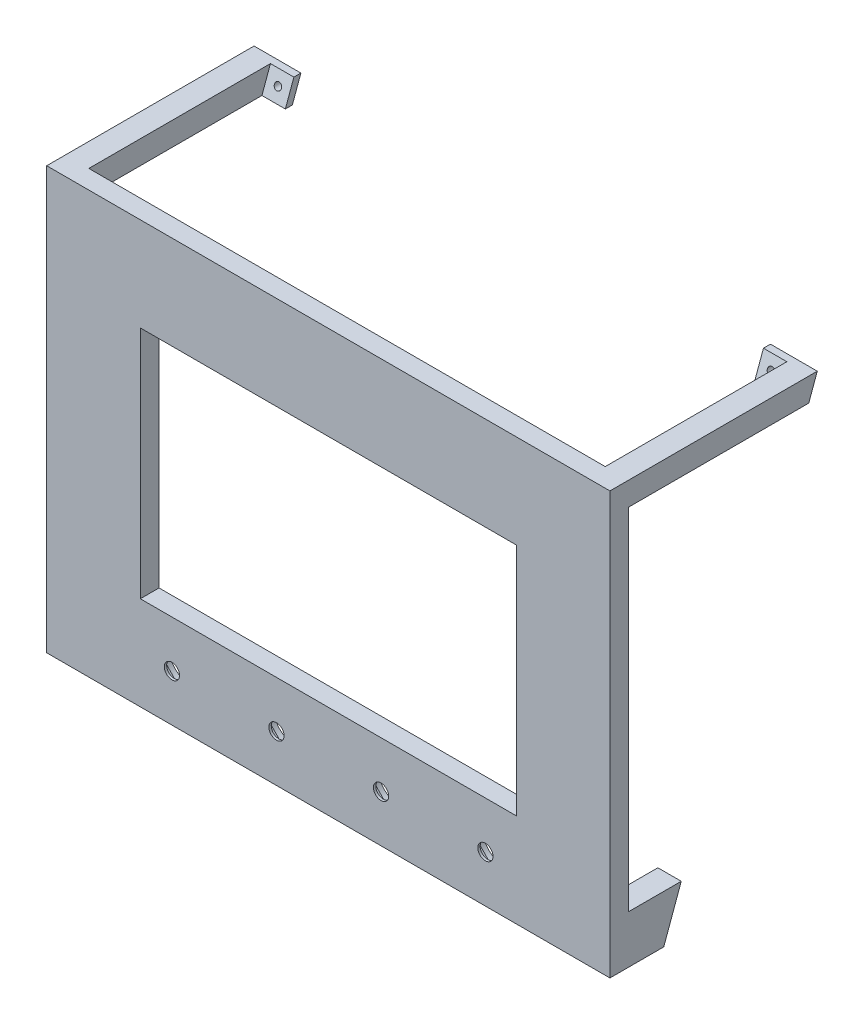
SolidWorks part; units mm, degrees
ref_plane "Front Plane" through (0, 0, 0) normal (0, 0, 1) x (1, 0, 0)
ref_plane "Top Plane" through (0, 0, 0) normal (0, 1, 0) x (1, 0, 0)
ref_plane "Right Plane" through (0, 0, 0) normal (1, 0, 0) x (0, 0, -1)
ref_plane "Plane1" through (0, 0, 0) normal (0, 0, -1) x (-1, 0, 0)
sketch "Sketch1" plane through (0, 0, 0) normal (0, 0, -1) x (-1, 0, 0)
  line L0 (69.5977, -77.75) -> (69.5977, 102.45)
  line L1 (69.5977, 102.45) -> (-171.0023, 102.45)
  line L2 (-171.0023, 102.45) -> (-171.0023, -77.75)
  line L3 (-171.0023, -77.75) -> (69.5977, -77.75)
extrude "Boss-Extrude1" add sketch "Sketch1" against normal blind 8
sketch "Sketch2" plane through (0, 0, 8) normal (0, 0, 1) x (1, 0, 0)
  line L0 (-29.5977, 62.45) -> (-29.5977, -37.75)
  line L1 (-29.5977, -37.75) -> (131.0023, -37.75)
  line L2 (131.0023, -37.75) -> (131.0023, 62.45)
  line L3 (131.0023, 62.45) -> (-29.5977, 62.45)
extrude "Cut-Extrude1" cut sketch "Sketch2" against normal through all
sketch "Sketch3" plane through (0, 0, 0) normal (0, 0, -1) x (-1, 0, 0)
  line L0 (-117.6868, -48.4833) -> (-127.0608, -58.1981)
  line L1 (-127.0608, -58.1981) -> (-117.9217, -67.0167)
  line L2 (-117.9217, -67.0167) -> (-108.5476, -57.3019)
  line L3 (-108.5476, -57.3019) -> (-117.6868, -48.4833)
extrude "Cut-Extrude2" cut sketch "Sketch3" against normal blind 7
sketch "Sketch4" plane through (0, 0, 0) normal (0, 0, -1) x (-1, 0, 0)
  line L0 (6.9392, -58.1981) -> (16.0783, -67.0167)
  line L1 (16.0783, -67.0167) -> (25.4524, -57.3019)
  line L2 (25.4524, -57.3019) -> (16.3132, -48.4833)
  line L3 (16.3132, -48.4833) -> (6.9392, -58.1981)
extrude "Cut-Extrude3" cut sketch "Sketch4" against normal blind 7
sketch "Sketch5" plane through (0, 0, 0) normal (0, 0, -1) x (-1, 0, 0)
  line L0 (-37.7275, -58.1981) -> (-28.5883, -67.0167)
  line L1 (-28.5883, -67.0167) -> (-19.2143, -57.3019)
  line L2 (-19.2143, -57.3019) -> (-28.3534, -48.4833)
  line L3 (-28.3534, -48.4833) -> (-37.7275, -58.1981)
extrude "Cut-Extrude4" cut sketch "Sketch5" against normal blind 7
sketch "Sketch6" plane through (0, 0, 0) normal (0, 0, -1) x (-1, 0, 0)
  line L0 (-82.3941, -58.1981) -> (-73.255, -67.0167)
  line L1 (-73.255, -67.0167) -> (-63.881, -57.3019)
  line L2 (-63.881, -57.3019) -> (-73.0201, -48.4833)
  line L3 (-73.0201, -48.4833) -> (-82.3941, -58.1981)
extrude "Cut-Extrude5" cut sketch "Sketch6" against normal blind 7
hole_wizard "Ø6.5 (6.5) Diameter Hole1" positions "Sketch8" profile "Sketch7" hole size "Ø6.5" standard "ANSI Metric"
sketch "Sketch8" plane through (0, 0, 8) normal (0, 0, 1) x (1, 0, 0)
  point P0 (117.8042, -57.75)
  point P1 (-16.0977, -57.75)
  point P2 (28.569, -57.75)
  point P3 (73.2357, -57.75)
sketch "Sketch7" plane through (117.8042, -57.75, 8) normal (1, 0, 0) x (0, -1, 0)
  line L0 (0, 0) -> (0, 8)
  line L1 (0, 8) -> (3.25, 8)
  line L2 (3.25, 8) -> (3.25, 0)
  line L5 (3.25, 0) -> (0, 0)
  line L11 (0, -6.35) -> (0, 107.95) construction
  dimension "Thru Hole Dia." = 6.5
  dimension "Thru Hole Depth" = 8
sketch "Sketch9" plane through (0, 0, 0) normal (0, 0, -1) x (-1, 0, 0)
  line L0 (-126.9808, -58.2753) -> (-117.9867, -66.9539)
  line L3 (-127.0608, -58.1981) -> (-117.9217, -67.0167) construction
  line L4 (-117.6868, -48.4833) -> (-108.5476, -57.3019)
  line L7 (-108.5476, -57.3019) -> (-117.6868, -48.4833) construction
  line L8 (-117.6868, -48.4833) -> (-127.0608, -58.1981) construction
  line L9 (-117.9217, -67.0167) -> (-108.5476, -57.3019) construction
  circle A0 centre (-117.8042, -57.75) radius 9.2674
  circle A1 centre (-73.2357, -57.75) radius 9.2692
  circle A2 centre (-28.569, -57.75) radius 9.2692
  circle A3 centre (16.0977, -57.75) radius 9.2667
  point P0 (-117.8042, -57.75)
  line M2 (-82.3941, -58.1981) -> (-73.0201, -48.4833)
  line M3 (-73.0201, -48.4833) -> (-63.881, -57.3019)
  line M4 (-63.881, -57.3019) -> (-73.255, -67.0167)
  line M5 (-73.255, -67.0167) -> (-82.3941, -58.1981)
  line M6 (-37.7275, -58.1981) -> (-28.3534, -48.4833)
  line M7 (-28.3534, -48.4833) -> (-19.2143, -57.3019)
  line M8 (-19.2143, -57.3019) -> (-28.5883, -67.0167)
  line M9 (-28.5883, -67.0167) -> (-37.7275, -58.1981)
  line M10 (6.9392, -58.1981) -> (16.3132, -48.4833)
  line M11 (16.3132, -48.4833) -> (25.4524, -57.3019)
  line M12 (25.4524, -57.3019) -> (16.0783, -67.0167)
  line M13 (16.0783, -67.0167) -> (6.9392, -58.1981)
  line M14 (-117.6868, -48.4833) -> (-108.5476, -57.3019)
  line M15 (-108.5476, -57.3019) -> (-117.9217, -67.0167)
  line M16 (-117.9217, -67.0167) -> (-127.0608, -58.1981)
  line M17 (-127.0608, -58.1981) -> (-117.6868, -48.4833)
extrude "Cut-Extrude7" cut sketch "Sketch9" against normal blind 4 contours A0 M14 | A0 M16 | A0 M17 | A0 M15 | A1 M2 M4 M5 | A1 M3 | A2 M6 M8 M9 | A2 M7 | A3 M10 M13 | A3 M12 | A3 M11
sketch "Sketch10" plane through (0, 0, 0) normal (0, 0, -1) x (-1, 0, 0)
  circle A0 centre (-127.0023, 69.25) radius 1.5
  circle A1 centre (29.9977, 69.25) radius 1.5
  circle A2 centre (29.9977, -45.75) radius 1.5
  circle A3 centre (-127.0023, -45.75) radius 1.5
sketch "Sketch12" plane through (171.0023, 0, 0) normal (1, 0, 0) x (0, 0, -1)
  line L0 (0, -77.75) -> (15, -77.75)
  line L1 (-8, -77.75) -> (0, -77.75) construction
  line L2 (0, 102.45) -> (0, -77.75) construction
  line L3 (0, -57.2038) -> (22.4782, -57.2038)
  line L4 (15, -77.75) -> (22.4782, -57.2038)
  line L5 (0, -77.75) -> (0, -57.2038)
  point P7 (31.7102, -57.2038)
  point P9 (29.881, -57.2038)
  dimension "D1" = 15
  dimension "D2" = 110
extrude "Boss-Extrude2" add sketch "Sketch12" against normal blind 10
sketch "Sketch14" plane through (-69.5977, 0, 0) normal (-1, 0, 0) x (0, 0, 1)
  line L0 (-22.4782, -57.2038) -> (-15, -77.75)
  line L1 (-15, -77.75) -> (0, -77.75)
  line L2 (0, -77.75) -> (0, -57.2038)
  line L3 (0, -57.2038) -> (-22.4782, -57.2038)
extrude "Boss-Extrude3" add sketch "Sketch14" against normal blind 10
ref_plane "Plane4" through (0, -13.9159, -38.2337) normal (0, -0.342, -0.9397) x (-1, 0, 0)
sketch "Sketch15" plane through (-69.5977, 0, 0) normal (-1, 0, 0) x (0, 0, 1)
  line L0 (0, 102.45) -> (-80.5874, 102.45)
  line L1 (-76.3387, 90.7768) -> (-0.1287, -118.6086) construction
  line L2 (0, 92.45) -> (-76.9477, 92.45)
  line L3 (0, -57.2038) -> (0, 102.45) construction
  line L4 (-76.9477, 92.45) -> (-80.5874, 102.45)
  line L11 (0, 102.45) -> (0, -57.2038)
  line L12 (0, -57.2038) -> (-22.4782, -57.2038)
  line L13 (-22.4782, -57.2038) -> (-15, -77.75)
  line L14 (-15, -77.75) -> (8, -77.75)
  line L15 (8, -77.75) -> (8, 102.45)
  line L16 (8, 102.45) -> (0, 102.45)
  line L17 (0, 102.45) -> (0, 92.45)
  dimension "D1" = 10
  dimension "D2" = 0
extrude "Boss-Extrude4" add sketch "Sketch15" against normal blind 10
sketch "Sketch16" plane through (171.0023, 0, 0) normal (1, 0, 0) x (0, 0, -1)
  line L0 (0, 102.45) -> (80.5874, 102.45)
  line L1 (0.1287, -118.6086) -> (76.3387, 90.7768) construction
  line L2 (0, 102.45) -> (80.5874, 102.45) construction
  line L3 (80.5874, 102.45) -> (76.9477, 92.45)
  line L4 (76.9477, 92.45) -> (0, 92.45) construction
  line L5 (76.9477, 92.45) -> (0, 92.45)
  line L6 (0, 92.45) -> (0, 102.45)
extrude "Boss-Extrude5" add sketch "Sketch16" against normal blind 10
sketch "Sketch18" plane through (0, -13.9159, -38.2337) normal (0, -0.342, -0.9397) x (-1, 0, 0)
  line L1 (59.5977, 113.1923) -> (49.5977, 113.1923)
  line L2 (59.5977, 123.834) -> (49.5977, 123.834)
  line L3 (-161.0023, 123.834) -> (-151.0023, 123.834)
  line L4 (-151.0023, 123.834) -> (-151.0023, 113.1923)
  line L5 (-161.0023, 113.1923) -> (-151.0023, 113.1923)
  line L6 (49.5977, 123.834) -> (49.5977, 113.1923)
  line L7 (59.5977, 113.1923) -> (59.5977, 123.834)
  line L8 (-161.0023, 113.1923) -> (-161.0023, 123.834)
  circle A1 centre (-156.0023, 118.5131) radius 1.5
  circle A2 centre (54.5977, 118.5131) radius 1.5
  dimension "D1" = 10
  dimension "D2" = 10
extrude "Boss-Extrude6" add sketch "Sketch18" along direction (0, 0, 1) on the side against the normal blind 3
